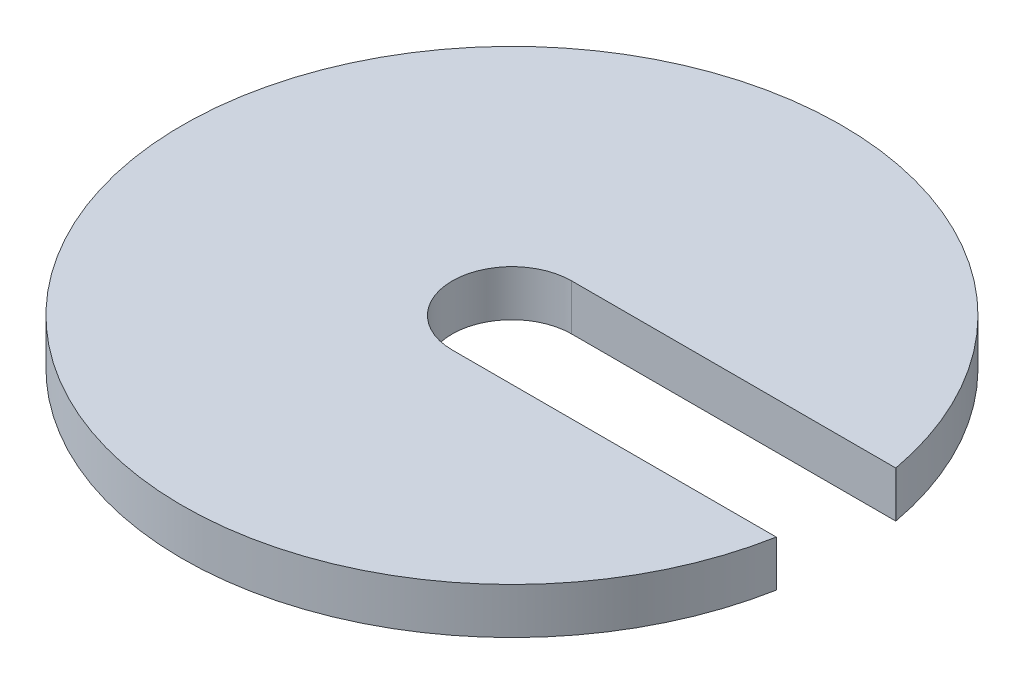
SolidWorks part; units mm, degrees
ref_plane "Front Plane" through (0, 0, 0) normal (0, 0, 1) x (1, 0, 0)
ref_plane "Top Plane" through (0, 0, 0) normal (0, 1, 0) x (1, 0, 0)
ref_plane "Right Plane" through (0, 0, 0) normal (1, 0, 0) x (0, 0, -1)
sketch "Sketch1" plane through (0, 0, 0) normal (0, 1, 0) x (1, 0, 0)
  line L0 (21.1251, 0) -> (0, 0) construction
  line L1 (-55, 0) -> (55, 0) construction
  line L2 (21.1251, -3.9) -> (0, -3.9)
  line L3 (21.1251, 3.9) -> (0, 3.9)
  arc A0 (21.1433, 3.9) -> (21.1433, -3.9) centre (0, 0) ccw
  arc A1 (21.1251, -3.9) -> (21.1433, -3.9) centre (21.1251, 0) ccw
  arc A2 (0, 3.9) -> (0, -3.9) centre (0, 0) ccw
  arc A3 (21.1433, 3.9) -> (21.1251, 3.9) centre (21.1251, 0) ccw
  point P4 (10.5625, 0)
  dimension "D1" = 43
  dimension "D2" = 3.9
extrude "Boss-Extrude1" add sketch "Sketch1" along normal blind 3
